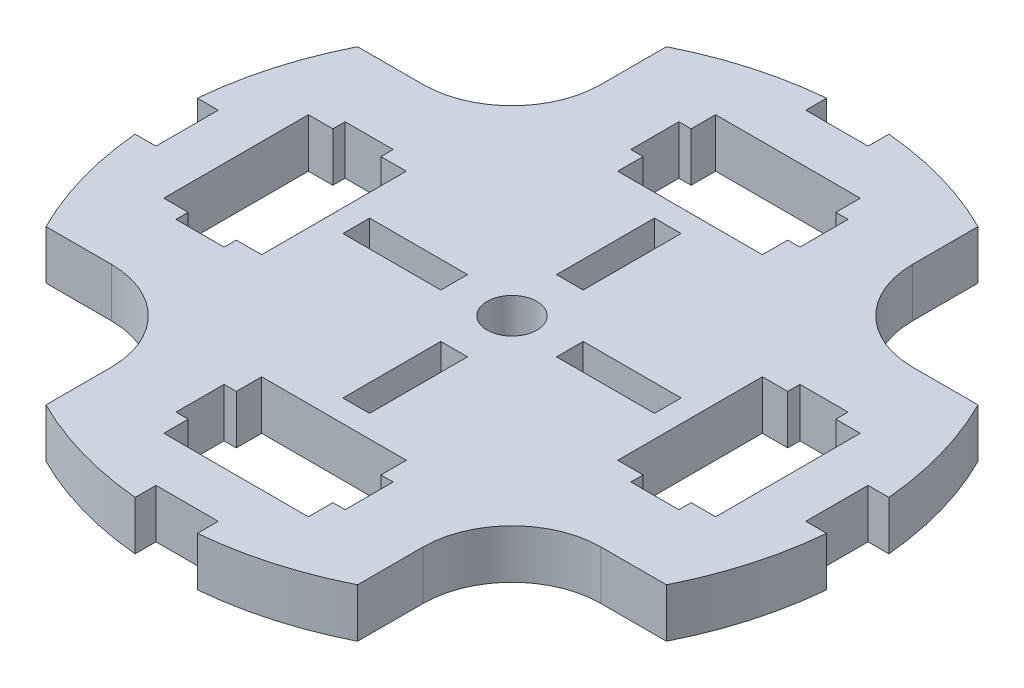
SolidWorks part; units mm, degrees
ref_plane "Front Plane" through (0, 0, 0) normal (0, 0, 1) x (1, 0, 0)
ref_plane "Top Plane" through (0, 0, 0) normal (0, 1, 0) x (1, 0, 0)
ref_plane "Right Plane" through (0, 0, 0) normal (1, 0, 0) x (0, 0, -1)
sketch "Sketch1" plane through (0, 0, 0) normal (0, 1, 0) x (1, 0, 0)
  line L0 (-8.125, 22.85) -> (-8.125, 20)
  line L1 (-1.5, 17.5) -> (1.5, 17.5)
  line L2 (-1.5, 17.5) -> (-1.5, 6.5)
  line L3 (-1.5, 6.5) -> (1.5, 6.5)
  line L4 (1.5, 17.5) -> (1.5, 6.5)
  line L5 (-8.125, 31) -> (8.125, 31)
  line L6 (-8.125, 31) -> (-8.125, 28.25)
  line L7 (-8.125, 20) -> (8.125, 20)
  line L8 (8.125, 31) -> (8.125, 28.25)
  line L9 (8.125, 28.25) -> (9.5, 28.25)
  line L10 (22.85, 8.125) -> (20, 8.125)
  line L11 (8.125, 22.85) -> (9.5, 22.85)
  line L12 (9.5, 28.25) -> (9.5, 22.85)
  line L13 (-8.125, 28.25) -> (-9.5, 28.25)
  line L14 (8.125, 22.85) -> (8.125, 20)
  line L15 (-8.125, 22.85) -> (-9.5, 22.85)
  line L16 (-9.5, 28.25) -> (-9.5, 22.85)
  line L17 (17.5, 1.5) -> (17.5, -1.5)
  line L18 (-3.5, 38.8426) -> (-3.5, 36.5)
  line L19 (-3.5, 36.5) -> (3.5, 36.5)
  line L20 (3.5, 38.8426) -> (3.5, 36.5)
  line L21 (17.5, 1.5) -> (6.5, 1.5)
  line L22 (6.5, 1.5) -> (6.5, -1.5)
  line L23 (17.5, -1.5) -> (6.5, -1.5)
  line L24 (31, 8.125) -> (31, -8.125)
  line L25 (31, 8.125) -> (28.25, 8.125)
  line L26 (20, 8.125) -> (20, -8.125)
  line L27 (31, -8.125) -> (28.25, -8.125)
  line L28 (28.25, -8.125) -> (28.25, -9.5)
  line L29 (22.85, -8.125) -> (22.85, -9.5)
  line L30 (28.25, -9.5) -> (22.85, -9.5)
  line L31 (28.25, 8.125) -> (28.25, 9.5)
  line L32 (22.85, -8.125) -> (20, -8.125)
  line L33 (22.85, 8.125) -> (22.85, 9.5)
  line L34 (28.25, 9.5) -> (22.85, 9.5)
  line L35 (38.8426, 3.5) -> (36.5, 3.5)
  line L36 (36.5, 3.5) -> (36.5, -3.5)
  line L37 (38.8426, -3.5) -> (36.5, -3.5)
  line L38 (8.125, -22.85) -> (8.125, -20)
  line L39 (1.5, -17.5) -> (-1.5, -17.5)
  line L40 (1.5, -17.5) -> (1.5, -6.5)
  line L41 (1.5, -6.5) -> (-1.5, -6.5)
  line L42 (-1.5, -17.5) -> (-1.5, -6.5)
  line L43 (8.125, -31) -> (-8.125, -31)
  line L44 (8.125, -31) -> (8.125, -28.25)
  line L45 (8.125, -20) -> (-8.125, -20)
  line L46 (-8.125, -31) -> (-8.125, -28.25)
  line L47 (-8.125, -28.25) -> (-9.5, -28.25)
  line L48 (-8.125, -22.85) -> (-9.5, -22.85)
  line L49 (-9.5, -28.25) -> (-9.5, -22.85)
  line L50 (8.125, -28.25) -> (9.5, -28.25)
  line L51 (-8.125, -22.85) -> (-8.125, -20)
  line L52 (8.125, -22.85) -> (9.5, -22.85)
  line L53 (9.5, -28.25) -> (9.5, -22.85)
  line L54 (3.5, -38.8426) -> (3.5, -36.5)
  line L55 (3.5, -36.5) -> (-3.5, -36.5)
  line L56 (-3.5, -38.8426) -> (-3.5, -36.5)
  line L57 (-22.85, -8.125) -> (-20, -8.125)
  line L58 (-17.5, -1.5) -> (-17.5, 1.5)
  line L59 (-17.5, -1.5) -> (-6.5, -1.5)
  line L60 (-6.5, -1.5) -> (-6.5, 1.5)
  line L61 (-17.5, 1.5) -> (-6.5, 1.5)
  line L62 (-31, -8.125) -> (-31, 8.125)
  line L63 (-31, -8.125) -> (-28.25, -8.125)
  line L64 (-20, -8.125) -> (-20, 8.125)
  line L65 (-31, 8.125) -> (-28.25, 8.125)
  line L66 (-28.25, 8.125) -> (-28.25, 9.5)
  line L67 (-22.85, 8.125) -> (-22.85, 9.5)
  line L68 (-28.25, 9.5) -> (-22.85, 9.5)
  line L69 (-28.25, -8.125) -> (-28.25, -9.5)
  line L70 (-22.85, 8.125) -> (-20, 8.125)
  line L71 (-22.85, -8.125) -> (-22.85, -9.5)
  line L72 (-28.25, -9.5) -> (-22.85, -9.5)
  line L73 (-38.8426, -3.5) -> (-36.5, -3.5)
  line L74 (-36.5, -3.5) -> (-36.5, 3.5)
  line L75 (-38.8426, 3.5) -> (-36.5, 3.5)
  line L76 (34.8533, -17.5) -> (17.5, -17.5)
  line L77 (17.5, -17.5) -> (17.5, -34.8533)
  line L78 (17.5, 34.8533) -> (17.5, 17.5)
  line L79 (17.5, 17.5) -> (34.8533, 17.5)
  line L80 (-17.5, -34.8533) -> (-17.5, -17.5)
  line L81 (-17.5, -17.5) -> (-34.8533, -17.5)
  line L82 (-34.8533, 17.5) -> (-17.5, 17.5)
  line L83 (-17.5, 17.5) -> (-17.5, 34.8533)
  arc A0 (-3.5, 38.8426) -> (-17.5, 34.8533) centre (0, 0) ccw
  circle A1 centre (0, 0) radius 2.8
  arc A2 (-38.8426, -3.5) -> (-34.8533, -17.5) centre (0, 0) ccw
  arc A3 (38.8426, 3.5) -> (34.8533, 17.5) centre (0, 0) ccw
  arc A4 (3.5, -38.8426) -> (17.5, -34.8533) centre (0, 0) ccw
  arc A5 (17.5, 34.8533) -> (3.5, 38.8426) centre (0, 0) ccw
  arc A6 (-34.8533, 17.5) -> (-38.8426, 3.5) centre (0, 0) ccw
  arc A7 (-17.5, -34.8533) -> (-3.5, -38.8426) centre (0, 0) ccw
  arc A8 (34.8533, -17.5) -> (38.8426, -3.5) centre (0, 0) ccw
  point P86 (0, 0)
  point P99 (0, 0)
  dimension "D1" = 78
  dimension "D2" = 5.6
  dimension "D3" = 3
  dimension "D4" = 6.5
  dimension "D5" = 1.5
  dimension "D6" = 11
  dimension "D7" = 16.25
  dimension "D8" = 11
  dimension "D9" = 8.125
  dimension "D10" = 2.5
  dimension "D11" = 5.4
  dimension "D12" = 1.375
  dimension "D13" = 2.75
  dimension "D14" = 1.375
  dimension "D15" = 5.4
  dimension "D16" = 2.75
  dimension "D17" = 7
  dimension "D18" = 3.5
  dimension "D19" = 5.5
  dimension "D21" = 8
  dimension "D22" = 8
  dimension "D20" = 4
  dimension "D23" = 4
extrude "Boss-Extrude1" add sketch "Sketch1" along normal blind 5.5
fillet "Fillet1" radius 10 1 edges at (-17.5, 2.75, 17.5)
fillet "Fillet2" radius 10 1 edges at (17.5, 2.75, 17.5)
fillet "Fillet3" radius 10 1 edges at (17.5, 2.75, -17.5)
fillet "Fillet4" radius 10 1 edges at (-17.5, 2.75, -17.5)
